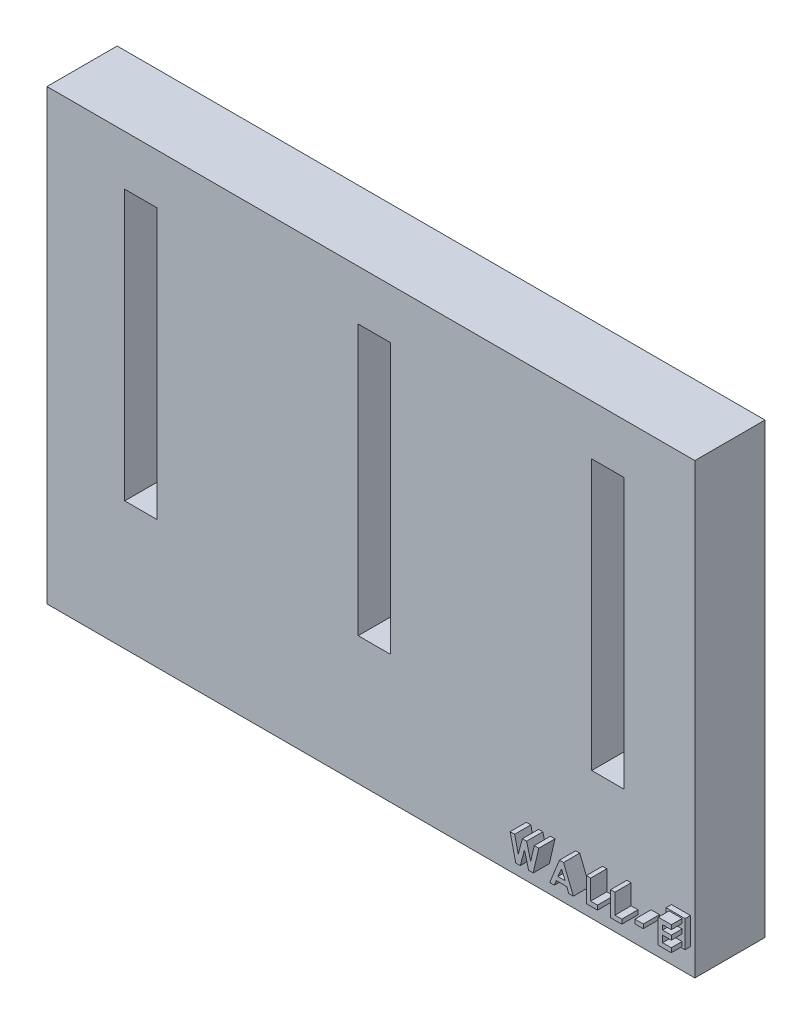
SolidWorks part; units mm, degrees
ref_plane "Front Plane" through (0, 0, 0) normal (0, 0, 1) x (1, 0, 0)
ref_plane "Top Plane" through (0, 0, 0) normal (0, 1, 0) x (1, 0, 0)
ref_plane "Right Plane" through (0, 0, 0) normal (1, 0, 0) x (0, 0, -1)
sketch "Sketch1" plane through (0, 0, 0) normal (0, 0, 1) x (1, 0, 0)
  line L1 (-60, -41.5) -> (60, -41.5)
  line L2 (-60, -41.5) -> (-60, 41.5)
  line L3 (-60, 41.5) -> (60, 41.5)
  line L4 (60, -41.5) -> (60, 41.5)
  line L5 (-60, -41.5) -> (60, 41.5) construction
  line L6 (-60, 41.5) -> (60, -41.5) construction
  point P0 (0, 0)
  dimension "D1" = 120
  dimension "D2" = 83
extrude "Boss-Extrude1" add sketch "Sketch1" along normal blind 13
sketch "Sketch2" plane through (0, 0, 13) normal (0, 0, 1) x (1, 0, 0)
  line L0 (-60, 41.5) -> (-60, 32.5) construction
  line L1 (-60, 41.5) -> (-60, -41.5) construction
  line L2 (-39.6022, -17.7686) -> (-2.3522, -17.7686) construction
  line L3 (-45.6022, 32.2314) -> (-39.6022, 32.2314)
  line L4 (-45.6022, 32.2314) -> (-45.6022, -17.7686)
  line L5 (-45.6022, -17.7686) -> (-39.6022, -17.7686)
  line L6 (-39.6022, 32.2314) -> (-39.6022, -17.7686)
  line L7 (-45.6022, 32.2314) -> (-39.6022, -17.7686) construction
  line L8 (-45.6022, -17.7686) -> (-39.6022, 32.2314) construction
  line L13 (3.6478, -17.7686) -> (40.8978, -17.7686) construction
  line L14 (-2.3522, -17.7686) -> (3.6478, -17.7686)
  line L19 (-2.3522, -17.7686) -> (-2.3522, 32.2314)
  line L20 (-2.3522, 32.2314) -> (3.6478, 32.2314)
  line L21 (3.6478, -17.7686) -> (3.6478, 32.2314)
  line L22 (-2.3522, -17.7686) -> (3.6478, 32.2314) construction
  line L23 (-2.3522, 32.2314) -> (3.6478, -17.7686) construction
  line L25 (40.8978, -17.7686) -> (46.8978, -17.7686)
  line L26 (40.8978, -17.7686) -> (40.8978, 32.2314)
  line L27 (40.8978, 32.2314) -> (46.8978, 32.2314)
  line L28 (46.8978, -17.7686) -> (46.8978, 32.2314)
  line L29 (40.8978, -17.7686) -> (46.8978, 32.2314) construction
  line L30 (40.8978, 32.2314) -> (46.8978, -17.7686) construction
  point P9 (-42.6022, 7.2314)
  point P15 (0.6478, 7.2314)
  point P20 (43.8978, 7.2314)
  dimension "D1" = 50
  dimension "D2" = 6
  dimension "D3" = 6
  dimension "D4" = 6
extrude "Cut-Extrude1" cut sketch "Sketch2" against normal blind 6
sketch "Sketch4" plane through (0, 0, 13) normal (0, 0, 1) x (1, 0, 0)
  line L0 (28.7011, -36.6301) -> (60, -36.6301) construction
  line L2 (60, -41.5) -> (60, 41.5) construction
  text T0 "<b>W A L L - E</b>" font "Century Gothic" height 4.5
extrude "Boss-Extrude3" add sketch "Sketch4" along normal blind 3
sketch "Sketch5" plane through (0, 0, 13) normal (0, 0, 1) x (1, 0, 0)
  line L0 (57.4318, -32.1301) -> (57.4318, -36.6301) construction
  line L1 (56.2203, -32.1301) -> (58.6434, -32.1301) construction
  line L2 (58.6434, -36.6301) -> (56.2203, -36.6301) construction
  line L3 (56.2203, -34.3801) -> (58.6434, -34.3801) construction
  line L4 (56.2203, -36.6301) -> (56.2203, -32.1301) construction
  line L5 (58.6434, -33.8031) -> (58.6434, -34.6108) construction
  line L7 (55.6818, -36.8801) -> (59.1818, -36.8801)
  line L8 (55.6818, -36.8801) -> (55.6818, -31.8801)
  line L9 (55.6818, -31.8801) -> (59.1818, -31.8801)
  line L10 (59.1818, -36.8801) -> (59.1818, -31.8801)
  line L11 (55.6818, -36.8801) -> (59.1818, -31.8801) construction
  line L12 (55.6818, -31.8801) -> (59.1818, -36.8801) construction
  point P12 (57.4318, -34.3801)
  dimension "D1" = 3.5
  dimension "D2" = 5
extrude "Boss-Extrude4" add sketch "Sketch5" along normal blind 1
